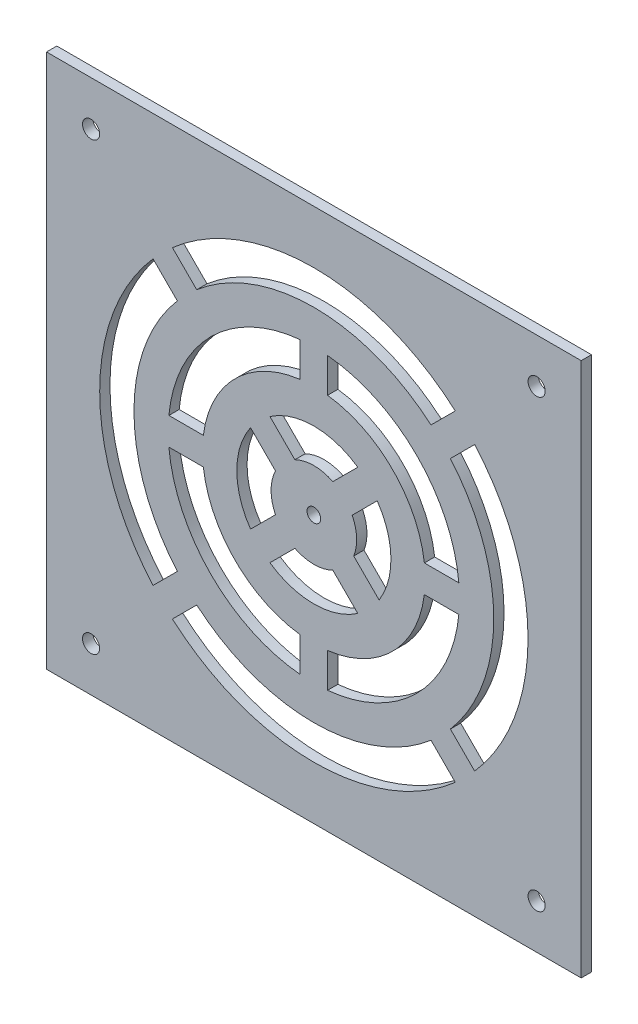
SolidWorks part; units mm, degrees
ref_plane "Front Plane" through (0, 0, 0) normal (0, 0, 1) x (1, 0, 0)
ref_plane "Top Plane" through (0, 0, 0) normal (0, 1, 0) x (1, 0, 0)
ref_plane "Right Plane" through (0, 0, 0) normal (1, 0, 0) x (0, 0, -1)
sketch "Sketch1" plane through (0, 0, 0) normal (0, 0, 1) x (1, 0, 0)
  line L1 (71.8966, -8.7931) -> (221.8966, -8.7931)
  line L2 (71.8966, -8.7931) -> (71.8966, 141.2069)
  line L3 (71.8966, 141.2069) -> (221.8966, 141.2069)
  line L4 (221.8966, -8.7931) -> (221.8966, 141.2069)
  line L5 (71.8966, -8.7931) -> (221.8966, 141.2069) construction
  line L6 (71.8966, 141.2069) -> (221.8966, -8.7931) construction
  dimension "D1" = 150
  dimension "D2" = 150
extrude "Boss-Extrude1" add sketch "Sketch1" along normal blind 3
sketch "Sketch2" plane through (0, 0, 3) normal (0, 0, 1) x (1, 0, 0)
  line L0 (99.9731, 107.4735) -> (107.0615, 100.3851)
  line L1 (146.8966, 141.2069) -> (146.8966, 128.6948) construction
  line L2 (221.8966, 141.2069) -> (71.8966, 141.2069) construction
  line L3 (146.8966, -8.7931) -> (146.8966, 3.719) construction
  line L4 (71.8966, -8.7931) -> (221.8966, -8.7931) construction
  line L5 (71.8966, 141.2069) -> (221.8966, -8.7931) construction
  line L6 (71.8966, -8.7931) -> (221.8966, 141.2069) construction
  line L7 (105.63, 113.1303) -> (112.7184, 106.0419)
  line L8 (109.1742, 109.5861) -> (106.3457, 106.7577) construction
  line L9 (106.3457, 106.7577) -> (103.5173, 103.9293) construction
  line L10 (187.4474, 25.6561) -> (184.6189, 22.8277) construction
  line L11 (190.2758, 28.4845) -> (187.4474, 25.6561) construction
  line L12 (193.82, 24.9403) -> (186.7316, 32.0287)
  line L13 (188.1631, 19.2835) -> (181.0747, 26.3719)
  line L14 (186.7316, 100.3851) -> (193.82, 107.4735)
  line L15 (181.0747, 106.0419) -> (188.1631, 113.1303)
  line L16 (184.6189, 109.5861) -> (187.4474, 106.7577) construction
  line L17 (187.4474, 106.7577) -> (190.2758, 103.9293) construction
  line L18 (106.3457, 25.6561) -> (109.1742, 22.8277) construction
  line L19 (103.5173, 28.4845) -> (106.3457, 25.6561) construction
  line L20 (112.7184, 26.3719) -> (105.63, 19.2835)
  line L21 (107.0615, 32.0287) -> (99.9731, 24.9403)
  line L22 (146.8966, 141.2069) -> (146.8966, -8.7931) construction
  line L23 (221.8966, 66.2069) -> (71.8966, 66.2069) construction
  line L24 (221.8966, -8.7931) -> (221.8966, 141.2069) construction
  line L25 (71.8966, 141.2069) -> (71.8966, -8.7931) construction
  line L26 (150.8966, 108.5061) -> (150.8966, 98.4476)
  line L27 (142.8966, 108.5061) -> (142.8966, 98.4476)
  line L28 (142.8966, 103.4769) -> (146.8966, 103.4769) construction
  line L29 (146.8966, 103.4769) -> (150.8966, 103.4769) construction
  line L30 (142.8966, 28.9369) -> (146.8966, 28.9369) construction
  line L31 (146.8966, 28.9369) -> (150.8966, 28.9369) construction
  line L32 (150.8966, 23.9077) -> (150.8966, 33.9662)
  line L33 (142.8966, 23.9077) -> (142.8966, 33.9662)
  line L34 (189.1957, 70.2069) -> (179.1373, 70.2069)
  line L35 (189.1957, 62.2069) -> (179.1373, 62.2069)
  line L36 (184.1665, 70.2069) -> (184.1665, 66.2069) construction
  line L37 (184.1665, 66.2069) -> (184.1665, 62.2069) construction
  line L38 (109.6266, 70.2069) -> (109.6266, 66.2069) construction
  line L39 (109.6266, 66.2069) -> (109.6266, 62.2069) construction
  line L40 (104.5974, 62.2069) -> (114.6558, 62.2069)
  line L41 (104.5974, 70.2069) -> (114.6558, 70.2069)
  line L42 (181.0747, 106.0419) -> (107.0615, 32.0287) construction
  line L43 (112.7184, 26.3719) -> (186.7316, 100.3851) construction
  line L44 (135.7031, 71.7435) -> (128.4204, 79.0262)
  line L45 (107.0615, 100.3851) -> (181.0747, 26.3719) construction
  line L46 (152.4332, 77.4004) -> (159.7159, 84.6831)
  line L47 (165.3728, 79.0262) -> (158.09, 71.7435)
  line L48 (141.3599, 55.0134) -> (134.0772, 47.7307)
  line L49 (135.7031, 60.6703) -> (128.4204, 53.3875)
  line L50 (158.5217, 61.6459) -> (165.9328, 54.2349)
  line L51 (159.7159, 47.7307) -> (152.4332, 55.0134)
  line L52 (134.0772, 84.6831) -> (141.3599, 77.4004)
  circle A1 centre (146.8966, 66.2069) radius 62.4879
  circle A2 centre (146.8966, 66.2069) radius 52.4879
  circle A3 centre (146.8966, 66.2069) radius 42.4879
  circle A4 centre (146.8966, 66.2069) radius 32.4879
  circle A5 centre (146.8966, 66.2069) radius 22.4879
  circle A6 centre (146.8966, 66.2069) radius 12.4879
  dimension "D1" = 10
  dimension "D3" = 10
  dimension "D7" = 10
  dimension "D9" = 10
  dimension "D10" = 10
  dimension "D4" = 8
  dimension "D5" = 8
  dimension "D6" = 8
  dimension "D8" = 8
  dimension "D11" = 8
extrude "Cut-Extrude1" cut sketch "Sketch2" against normal through all contours A2 L15 A1 L7 | A2 L0 A1 L21 | A2 L12 A1 L14 | A2 L20 A1 L13 | A4 L32 A3 L35 | A4 L40 A3 L33 | A4 L27 A3 L41 | A4 L34 A3 L26 | A6 L50 A5 L47 | A6 L46 A5 L52 | A6 L44 A5 L49 | A6 L48 A5 L51
sketch "Sketch4" plane through (0, 0, 3) normal (0, 0, 1) x (1, 0, 0)
  line L0 (81.8966, 141.2069) -> (81.8966, 131.2069) construction
  line L1 (221.8966, 141.2069) -> (71.8966, 141.2069) construction
  line L2 (81.8966, 131.2069) -> (71.8966, 131.2069) construction
  line L3 (71.8966, 141.2069) -> (71.8966, -8.7931) construction
  circle A1 centre (81.8966, 131.2069) radius 2.5
  circle A2 centre (211.8966, 131.2069) radius 2.5
  circle A3 centre (211.8966, 1.2069) radius 2.5
  circle A4 centre (81.8966, 1.2069) radius 2.5
  point P17 (146.8966, 66.2069)
  dimension "D2" = 5
  dimension "D1" = 10
  dimension "D3" = 4
extrude "Cut-Extrude2" cut sketch "Sketch4" against normal blind 3
sketch "Sketch5" plane through (0, 0, 0) normal (0, 0, -1) x (-1, 0, 0)
  line L9 (-221.8966, -8.7931) -> (-71.8966, -8.7931)
  line L10 (-71.8966, -8.7931) -> (-71.8966, 141.2069)
  line L11 (-224.8966, 144.2069) -> (-68.8966, 144.2069)
  line L12 (-224.8966, 144.2069) -> (-224.8966, -11.7931)
  line L21 (-224.8966, -11.7931) -> (-68.8966, -11.7931)
  line L22 (-68.8966, 144.2069) -> (-68.8966, -11.7931)
  line L23 (-71.8966, 141.2069) -> (-221.8966, 141.2069)
  line L24 (-221.8966, 141.2069) -> (-221.8966, -8.7931)
  point P1 (-146.8966, 66.2069)
  dimension "D1" = 156
  dimension "D4" = 156
extrude "Boss-Extrude2" add sketch "Sketch5" against normal blind 3 contours L22 L11 L12 L21 L24 L23 L10 L9
sketch "Sketch6" plane through (0, 0, 3) normal (0, 0, 1) x (1, 0, 0)
  circle A0 centre (146.8966, 66.2069) radius 2
extrude "Cut-Extrude3" cut sketch "Sketch6" against normal blind 10
